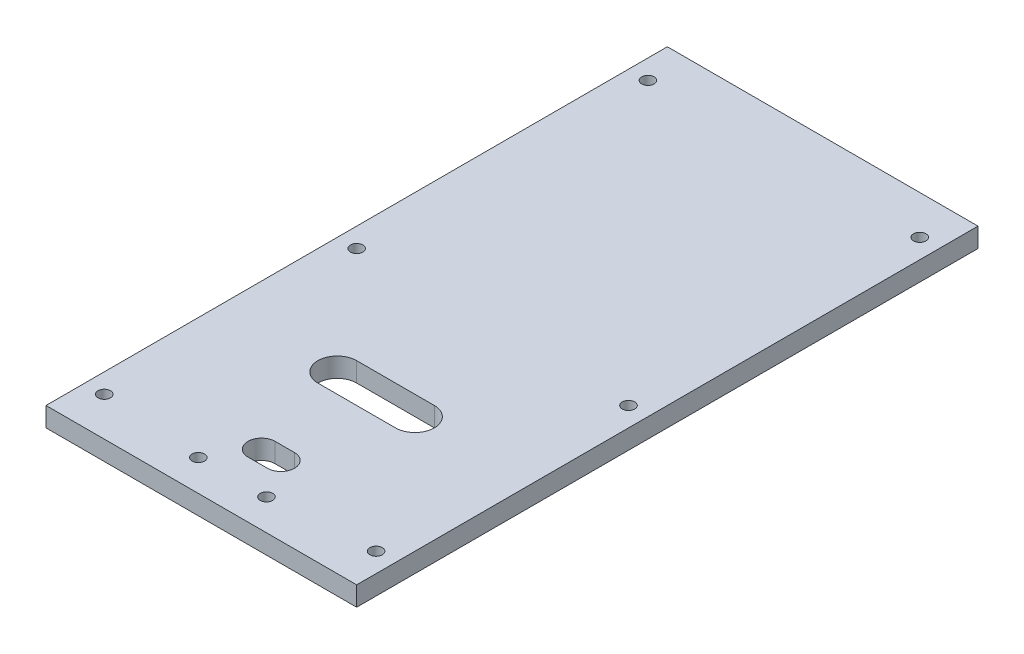
SolidWorks part; units mm, degrees
ref_plane "Plan de face" through (0, 0, 0) normal (0, 0, 1) x (1, 0, 0)
ref_plane "Plan de dessus" through (0, 0, 0) normal (0, 1, 0) x (1, 0, 0)
ref_plane "Plan de droite" through (0, 0, 0) normal (1, 0, 0) x (0, 0, -1)
sketch "Esquisse1" plane through (0, 0, 0) normal (0, 1, 0) x (1, 0, 0)
  line L1 (0, 0) -> (80, 0)
  line L2 (0, 0) -> (0, 160)
  line L3 (0, 160) -> (80, 160)
  line L4 (80, 0) -> (80, 160)
  dimension "D1" = 160
  dimension "D2" = 80
extrude "Boss.-Extru.1" add sketch "Esquisse1" along normal blind 5
sketch "Esquisse2" plane through (0, 0, 0) normal (0, 1, 0) x (1, 0, 0)
  line L0 (5, 160) -> (5, 0) construction
  line L1 (80, 160) -> (0, 160) construction
  line L2 (0, 0) -> (80, 0) construction
  line L3 (0, 160) -> (0, 0) construction
  line L4 (40, 160) -> (40, 0) construction
  circle A0 centre (5, 150) radius 1.6
  circle A1 centre (5, 75) radius 1.6
  circle A2 centre (5, 10) radius 1.6
  circle A3 centre (75, 10) radius 1.6
  circle A4 centre (75, 75) radius 1.6
  circle A5 centre (75, 150) radius 1.6
  dimension "D1" = 3.2
  dimension "D2" = 5
  dimension "D3" = 10
  dimension "D4" = 10
  dimension "D5" = 75
extrude "Enlèv. mat.-Extru.8" cut sketch "Esquisse2" along normal blind 10
sketch "Esquisse3" plane through (0, 0, 0) normal (0, 1, 0) x (1, 0, 0)
  line L0 (0, 8) -> (80, 8) construction
  line L1 (0, 160) -> (0, 0) construction
  line L2 (80, 0) -> (80, 160) construction
  line L3 (40, 160) -> (40, 0) construction
  line L4 (80, 160) -> (0, 160) construction
  line L5 (0, 0) -> (80, 0) construction
  circle A0 centre (31.225, 8) radius 1.6
  circle A1 centre (48.775, 8) radius 1.6
  dimension "D1" = 3.2
  dimension "D2" = 8.775
  dimension "D3" = 8
extrude "Enlèv. mat.-Extru.10" cut sketch "Esquisse3" along normal blind 10
sketch "Esquisse4" plane through (0, 5, 0) normal (0, 1, 0) x (1, 0, 0)
  line L0 (40, 160) -> (40, 0) construction
  line L1 (80, 160) -> (0, 160) construction
  line L2 (0, 0) -> (80, 0) construction
  line L3 (37.5, 18) -> (42.5, 18) construction
  line L4 (37.5, 21.5) -> (42.5, 21.5)
  line L5 (37.5, 14.5) -> (42.5, 14.5)
  line L6 (30, 45) -> (50, 45) construction
  line L7 (30, 50) -> (50, 50)
  line L8 (30, 40) -> (50, 40)
  arc A0 (37.5, 21.5) -> (37.5, 14.5) centre (37.5, 18) ccw
  arc A1 (42.5, 14.5) -> (42.5, 21.5) centre (42.5, 18) ccw
  arc A2 (30, 50) -> (30, 40) centre (30, 45) ccw
  arc A3 (50, 40) -> (50, 50) centre (50, 45) ccw
  point P8 (40, 18)
  point P14 (40, 45)
  dimension "D2" = 5
  dimension "D5" = 7
  dimension "D1" = 40
  dimension "D3" = 20
  dimension "D4" = 5
  dimension "D6" = 18
extrude "Enlèv. mat.-Extru.11" cut sketch "Esquisse4" against normal through all
